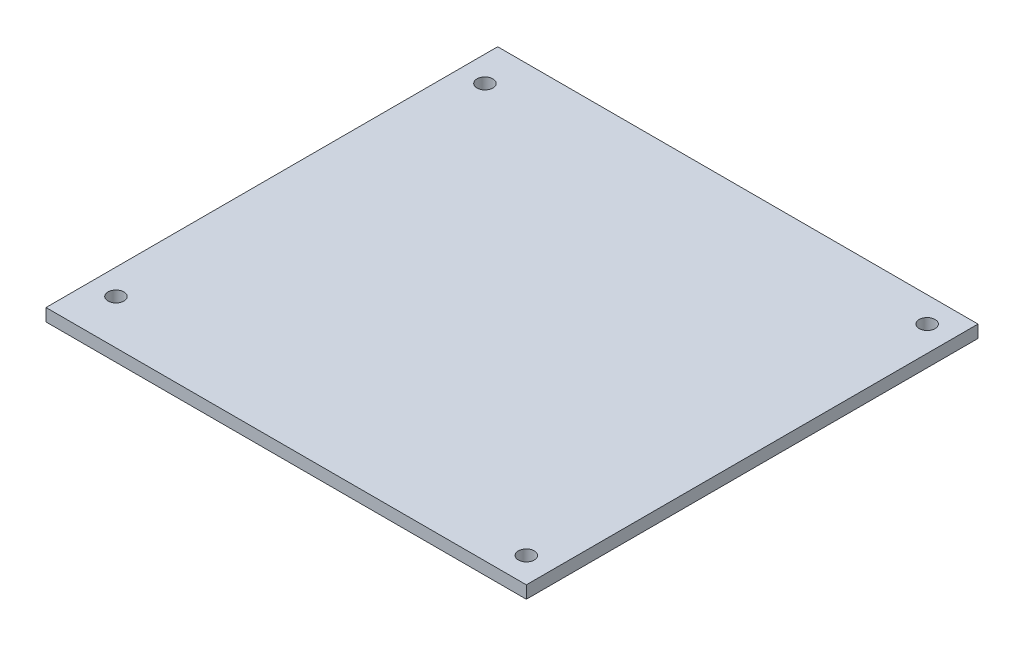
SolidWorks part; units mm, degrees
material "6061 Alloy"
ref_plane "Front Plane" through (0, 0, 0) normal (0, 0, 1) x (1, 0, 0)
ref_plane "Top Plane" through (0, 0, 0) normal (0, 1, 0) x (1, 0, 0)
ref_plane "Right Plane" through (0, 0, 0) normal (1, 0, 0) x (0, 0, -1)
sketch "Sketch1" plane through (0, 0, 0) normal (0, 1, 0) x (1, 0, 0)
  line L0 (0, 0) -> (95.89, 0)
  line L1 (0, 0) -> (0, 90.17)
  line L2 (95.89, 0) -> (95.89, 90.17)
  line L3 (0, 90.17) -> (95.89, 90.17)
  dimension "D1" = 95.89
  dimension "D2" = 90.17
extrude "Boss-Extrude1" add sketch "Sketch1" along normal blind 2.5
hole_wizard "Ø1.0mm Dowel Hole1" positions "3DSketch1" profile "Sketch2" hole size "Ø1.0" standard "ANSI Metric" end condition through all
sketch3d "3DSketch1"
  line L0 (95.89, 2.5, -90.17) -> (0, 2.5, -90.17) construction
  line L1 (0, 2.5, -90.17) -> (0, 2.5, 0) construction
  line L2 (0, 2.5, 0) -> (95.89, 2.5, 0) construction
  line L3 (95.89, 2.5, 0) -> (95.89, 2.5, -90.17) construction
  point P0 (5.08, 2.5, -82.55)
  point P2 (5.08, 2.5, -8.89)
  point P4 (90.81, 2.5, -85.09)
  point P6 (90.81, 2.5, -5.08)
  dimension "D1" = 7.62
  dimension "D2" = 5.08
  dimension "D3" = 8.89
  dimension "D4" = 5.08
  dimension "D5" = 5.08
  dimension "D6" = 5.08
  dimension "D7" = 5.08
  dimension "D8" = 5.08
sketch "Sketch2" plane through (5.08, 2.5, -82.55) normal (1, 0, 0) x (0, 0, 1)
  line L0 (0, 0) -> (0, 2.5)
  line L1 (0, 2.5) -> (1.59, 2.5)
  line L2 (1.59, 2.5) -> (1.59, 0)
  line L5 (1.59, 0) -> (0, 0)
  line L11 (0, -6.35) -> (0, 107.95) construction
  dimension "Thru Hole Dia." = 3.18
  dimension "Thru Hole Depth" = 2.5
